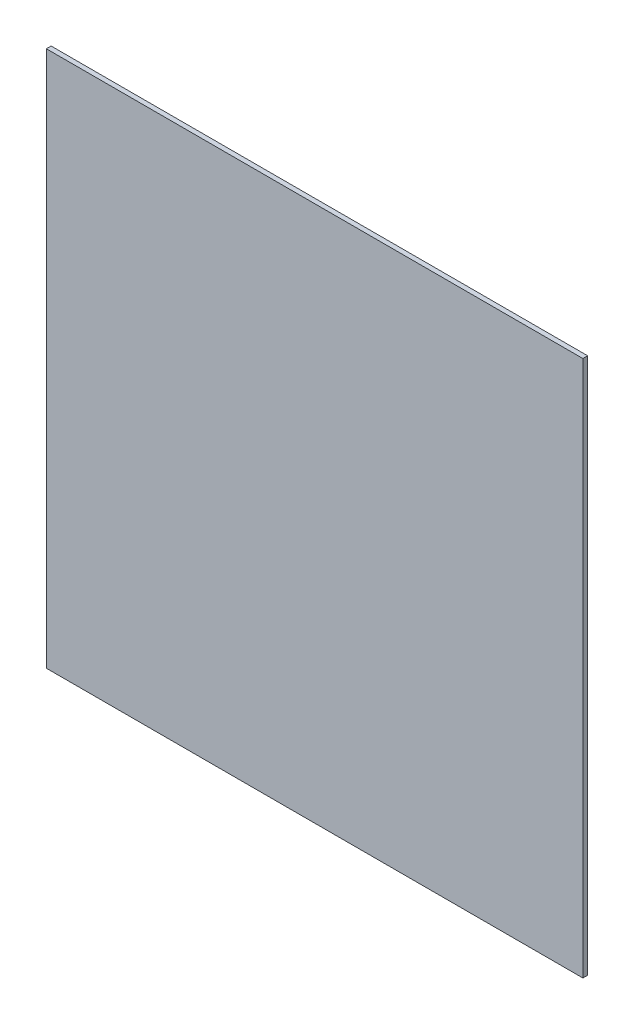
SolidWorks part; units mm, degrees
material "3003 Alloy"
ref_plane "Front Plane" through (0, 0, 0) normal (0, 0, 1) x (1, 0, 0)
ref_plane "Top Plane" through (0, 0, 0) normal (0, 1, 0) x (1, 0, 0)
ref_plane "Right Plane" through (0, 0, 0) normal (1, 0, 0) x (0, 0, -1)
sketch "Sketch1" plane through (0, 0, 0) normal (0, 0, 1) x (1, 0, 0)
  line L1 (112.3, -112.3) -> (-112.3, -112.3)
  line L2 (112.3, -112.3) -> (112.3, 112.3)
  line L3 (112.3, 112.3) -> (-112.3, 112.3)
  line L4 (-112.3, -112.3) -> (-112.3, 112.3)
  line L5 (112.3, -112.3) -> (-112.3, 112.3) construction
  line L6 (112.3, 112.3) -> (-112.3, -112.3) construction
  point P0 (0, 0)
  dimension "D1" = 224.6
  dimension "D2" = 224.6
extrude "Boss-Extrude1" add sketch "Sketch1" along normal blind 2
